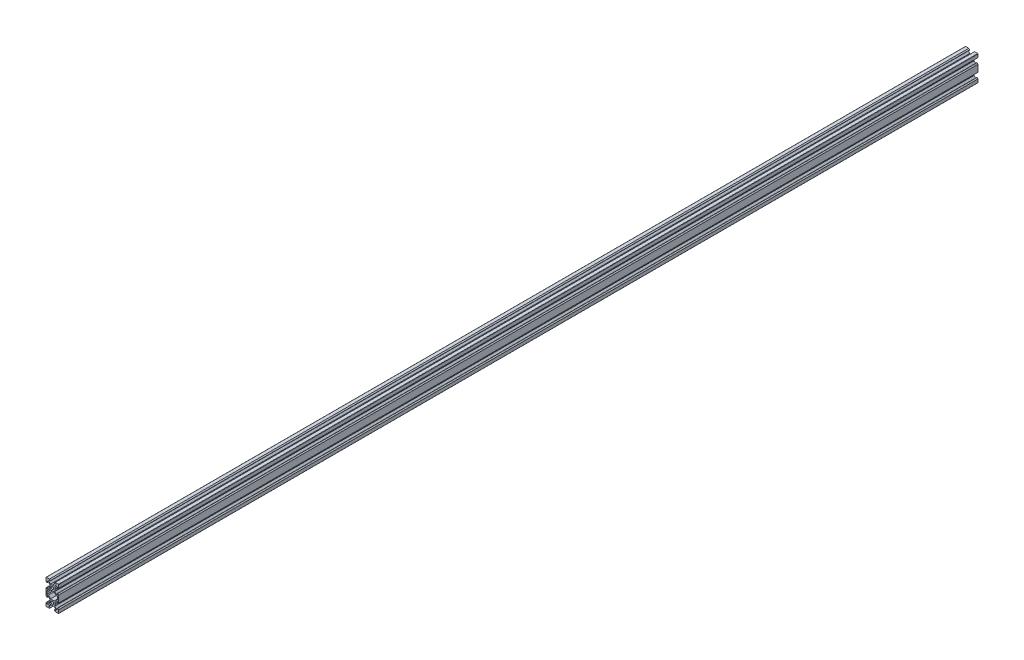
SolidWorks part; units mm, degrees
material "6061-T6 (SS)"
ref_plane "Front Plane" through (0, 0, 0) normal (0, 0, 1) x (1, 0, 0)
ref_plane "Top Plane" through (0, 0, 0) normal (0, 1, 0) x (1, 0, 0)
ref_plane "Right Plane" through (0, 0, 0) normal (1, 0, 0) x (0, 0, -1)
sketch "Sketch1" plane through (0, 0, 0) normal (0, 0, 1) x (1, 0, 0)
  line L0 (0, 0) -> (10, 0) construction
  line L1 (9.5, -20) -> (-9.5, -20)
  line L2 (10, -19.5) -> (10, 19.5)
  line L3 (9.5, 20) -> (-9.5, 20)
  line L4 (-10, -19.5) -> (-10, 19.5)
  line L5 (10, -20) -> (-10, 20) construction
  line L6 (10, 20) -> (-10, -20) construction
  circle A0 centre (0, 10) radius 2.1
  circle A1 centre (0, -10) radius 2.1
  arc A2 (-9.5, -20) -> (-10, -19.5) centre (-9.5, -19.5) cw
  arc A3 (9.5, -20) -> (10, -19.5) centre (9.5, -19.5) ccw
  arc A4 (10, 19.5) -> (9.5, 20) centre (9.5, 19.5) ccw
  arc A5 (-9.5, 20) -> (-10, 19.5) centre (-9.5, 19.5) ccw
  point P0 (0, 0)
  line B0 (0, 10) -> (0, 20) construction
  line B1 (0, 13.69) -> (-0.21, 13.9)
  line B2 (-0.21, 13.9) -> (-2.8393, 13.9)
  line B3 (-2.8393, 13.9) -> (-5.5, 16.5607)
  line B4 (-5.5, 16.5607) -> (-5.5, 18.2)
  line B5 (-5.5, 18.2) -> (-3.125, 18.2)
  line B6 (-3.125, 18.2) -> (-3.125, 18.545)
  line B7 (-3.125, 18.545) -> (-4.58, 20)
  line B8 (-4.58, 20) -> (4.58, 20)
  line B9 (0, 10) -> (-5.9132, 15.9132) construction
  line B10 (3.125, 18.545) -> (4.58, 20)
  line B11 (3.125, 18.2) -> (3.125, 18.545)
  line B12 (5.5, 18.2) -> (3.125, 18.2)
  line B13 (5.5, 16.5607) -> (5.5, 18.2)
  line B14 (2.8393, 13.9) -> (5.5, 16.5607)
  line B15 (0.21, 13.9) -> (2.8393, 13.9)
  line B16 (0, 13.69) -> (0.21, 13.9)
  line B17 (0, 10) -> (-10, 10) construction
  line B18 (-3.69, 10) -> (-3.9, 9.79)
  line B19 (-3.9, 9.79) -> (-3.9, 7.1607)
  line B20 (-3.9, 7.1607) -> (-6.5607, 4.5)
  line B21 (-6.5607, 4.5) -> (-8.2, 4.5)
  line B22 (-8.2, 4.5) -> (-8.2, 6.875)
  line B23 (-8.2, 6.875) -> (-8.545, 6.875)
  line B24 (-8.545, 6.875) -> (-10, 5.42)
  line B25 (-10, 5.42) -> (-10, 14.58)
  line B26 (0, 10) -> (-5.9132, 4.0868) construction
  line B27 (-8.545, 13.125) -> (-10, 14.58)
  line B28 (-8.2, 13.125) -> (-8.545, 13.125)
  line B29 (-8.2, 15.5) -> (-8.2, 13.125)
  line B30 (-6.5607, 15.5) -> (-8.2, 15.5)
  line B31 (-3.9, 12.8393) -> (-6.5607, 15.5)
  line B32 (-3.9, 10.21) -> (-3.9, 12.8393)
  line B33 (-3.69, 10) -> (-3.9, 10.21)
  line B34 (0, -10) -> (-10, -10) construction
  line B35 (-3.69, -10) -> (-3.9, -10.21)
  line B36 (-3.9, -10.21) -> (-3.9, -12.8393)
  line B37 (-3.9, -12.8393) -> (-6.5607, -15.5)
  line B38 (-6.5607, -15.5) -> (-8.2, -15.5)
  line B39 (-8.2, -15.5) -> (-8.2, -13.125)
  line B40 (-8.2, -13.125) -> (-8.545, -13.125)
  line B41 (-8.545, -13.125) -> (-10, -14.58)
  line B42 (-10, -14.58) -> (-10, -5.42)
  line B43 (0, -10) -> (-5.9132, -15.9132) construction
  line B44 (-8.545, -6.875) -> (-10, -5.42)
  line B45 (-8.2, -6.875) -> (-8.545, -6.875)
  line B46 (-8.2, -4.5) -> (-8.2, -6.875)
  line B47 (-6.5607, -4.5) -> (-8.2, -4.5)
  line B48 (-3.9, -7.1607) -> (-6.5607, -4.5)
  line B49 (-3.9, -9.79) -> (-3.9, -7.1607)
  line B50 (-3.69, -10) -> (-3.9, -9.79)
  line B51 (0, -10) -> (0, -20) construction
  line B52 (0, -13.69) -> (0.21, -13.9)
  line B53 (0.21, -13.9) -> (2.8393, -13.9)
  line B54 (2.8393, -13.9) -> (5.5, -16.5607)
  line B55 (5.5, -16.5607) -> (5.5, -18.2)
  line B56 (5.5, -18.2) -> (3.125, -18.2)
  line B57 (3.125, -18.2) -> (3.125, -18.545)
  line B58 (3.125, -18.545) -> (4.58, -20)
  line B59 (4.58, -20) -> (-4.58, -20)
  line B60 (0, -10) -> (5.9132, -15.9132) construction
  line B61 (-3.125, -18.545) -> (-4.58, -20)
  line B62 (-3.125, -18.2) -> (-3.125, -18.545)
  line B63 (-5.5, -18.2) -> (-3.125, -18.2)
  line B64 (-5.5, -16.5607) -> (-5.5, -18.2)
  line B65 (-2.8393, -13.9) -> (-5.5, -16.5607)
  line B66 (-0.21, -13.9) -> (-2.8393, -13.9)
  line B67 (0, -13.69) -> (-0.21, -13.9)
  line B68 (0, -10) -> (10, -10) construction
  line B69 (3.69, -10) -> (3.9, -9.79)
  line B70 (3.9, -9.79) -> (3.9, -7.1607)
  line B71 (3.9, -7.1607) -> (6.5607, -4.5)
  line B72 (6.5607, -4.5) -> (8.2, -4.5)
  line B73 (8.2, -4.5) -> (8.2, -6.875)
  line B74 (8.2, -6.875) -> (8.545, -6.875)
  line B75 (8.545, -6.875) -> (10, -5.42)
  line B76 (10, -5.42) -> (10, -14.58)
  line B77 (0, -10) -> (5.9132, -4.0868) construction
  line B78 (8.545, -13.125) -> (10, -14.58)
  line B79 (8.2, -13.125) -> (8.545, -13.125)
  line B80 (8.2, -15.5) -> (8.2, -13.125)
  line B81 (6.5607, -15.5) -> (8.2, -15.5)
  line B82 (3.9, -12.8393) -> (6.5607, -15.5)
  line B83 (3.9, -10.21) -> (3.9, -12.8393)
  line B84 (3.69, -10) -> (3.9, -10.21)
  line B85 (0, 10) -> (10, 10) construction
  line B86 (3.69, 10) -> (3.9, 10.21)
  line B87 (3.9, 10.21) -> (3.9, 12.8393)
  line B88 (3.9, 12.8393) -> (6.5607, 15.5)
  line B89 (6.5607, 15.5) -> (8.2, 15.5)
  line B90 (8.2, 15.5) -> (8.2, 13.125)
  line B91 (8.2, 13.125) -> (8.545, 13.125)
  line B92 (8.545, 13.125) -> (10, 14.58)
  line B93 (10, 14.58) -> (10, 5.42)
  line B94 (0, 10) -> (5.9132, 15.9132) construction
  line B95 (8.545, 6.875) -> (10, 5.42)
  line B96 (8.2, 6.875) -> (8.545, 6.875)
  line B97 (8.2, 4.5) -> (8.2, 6.875)
  line B98 (6.5607, 4.5) -> (8.2, 4.5)
  line B99 (3.9, 7.1607) -> (6.5607, 4.5)
  line B100 (3.9, 9.79) -> (3.9, 7.1607)
  line B101 (3.69, 10) -> (3.9, 9.79)
  line B102 (-8.2, -2.7) -> (-8.2, 2.7)
  line B103 (-8.2, 2.7) -> (-6.2393, 2.7)
  line B104 (-6.2393, 2.7) -> (-2.8393, 6.1)
  line B105 (-2.8393, 6.1) -> (2.8393, 6.1)
  line B106 (0, 6.1) -> (0, 0) construction
  line B107 (0, 0) -> (-8.2, 0) construction
  line B108 (6.2393, 2.7) -> (2.8393, 6.1)
  line B109 (8.2, 2.7) -> (6.2393, 2.7)
  line B110 (8.2, -2.7) -> (8.2, 2.7)
  line B111 (8.2, -2.7) -> (6.2393, -2.7)
  line B112 (6.2393, -2.7) -> (2.8393, -6.1)
  line B113 (-2.8393, -6.1) -> (2.8393, -6.1)
  line B114 (-6.2393, -2.7) -> (-2.8393, -6.1)
  line B115 (-8.2, -2.7) -> (-6.2393, -2.7)
  line B116 (0, 6.1) -> (0, 10) construction
  line B117 (0, 10) -> (-5.0927, 4.9073) construction
  dimension "D4" = 4.2
  dimension "D5" = 0.5
  dimension "D1" = 20
  dimension "D2" = 40
  dimension "D3" = 20
sketch_block_instance "V Slot 1-4"
sketch_block "V Slot 1" parameters "D1"=10, "D2"=11, "D3"=4.3, "D4"=1.8, "D5"=0.21, "D6"=45, "D7"=9.16, "D8"=1.5, "D9"=6.25
sketch_block_instance "V Slot 1-5"
sketch_block_instance "V Slot 1-6"
sketch_block_instance "V Slot 1-7"
sketch_block_instance "V Slot 1-8"
sketch_block_instance "V Slot 1-9"
sketch_block_instance "Center Cutout 1-1"
sketch_block "Center Cutout 1" parameters "D1"=5.4, "D2"=12.2, "D3"=8.2, "D4"=45, "D5"=10, "D6"=1.5
extrude "Boss-Extrude1" add sketch "Sketch1" along normal blind 1447.8 contours B101 B86 B87 B88 B89 B90 B91 B92 L2 A4 L3 B10 B11 B12 B13 B14 B15 B16 B1 B2 B3 B4 B5 B6 B7 A5 L4 B27 B28 B29 B30 B31 B32 B33 B18 B19 B20 B21 B22 B23 B24 B44 B45 B46 B47 B48 B49 B50 B35
